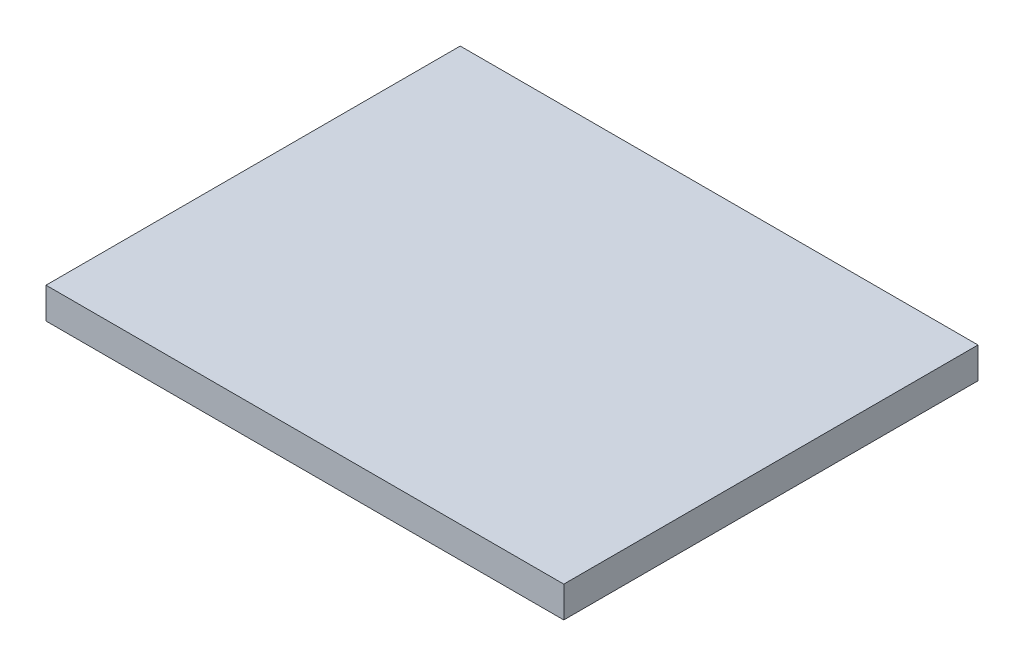
SolidWorks part; units mm, degrees
ref_plane "Front Plane" through (0, 0, 0) normal (0, 0, 1) x (1, 0, 0)
ref_plane "Top Plane" through (0, 0, 0) normal (0, 1, 0) x (1, 0, 0)
ref_plane "Right Plane" through (0, 0, 0) normal (1, 0, 0) x (0, 0, -1)
sketch "Sketch1" plane through (0, 0, 0) normal (0, 1, 0) x (1, 0, 0)
  line L1 (-25, 20) -> (25, 20)
  line L2 (-25, 20) -> (-25, -20)
  line L3 (-25, -20) -> (25, -20)
  line L4 (25, 20) -> (25, -20)
  line L5 (-25, 20) -> (25, -20) construction
  line L6 (-25, -20) -> (25, 20) construction
  point P0 (0, 0)
  dimension "D1" = 40
  dimension "D2" = 50
extrude "Boss-Extrude1" add sketch "Sketch1" along normal blind 3
